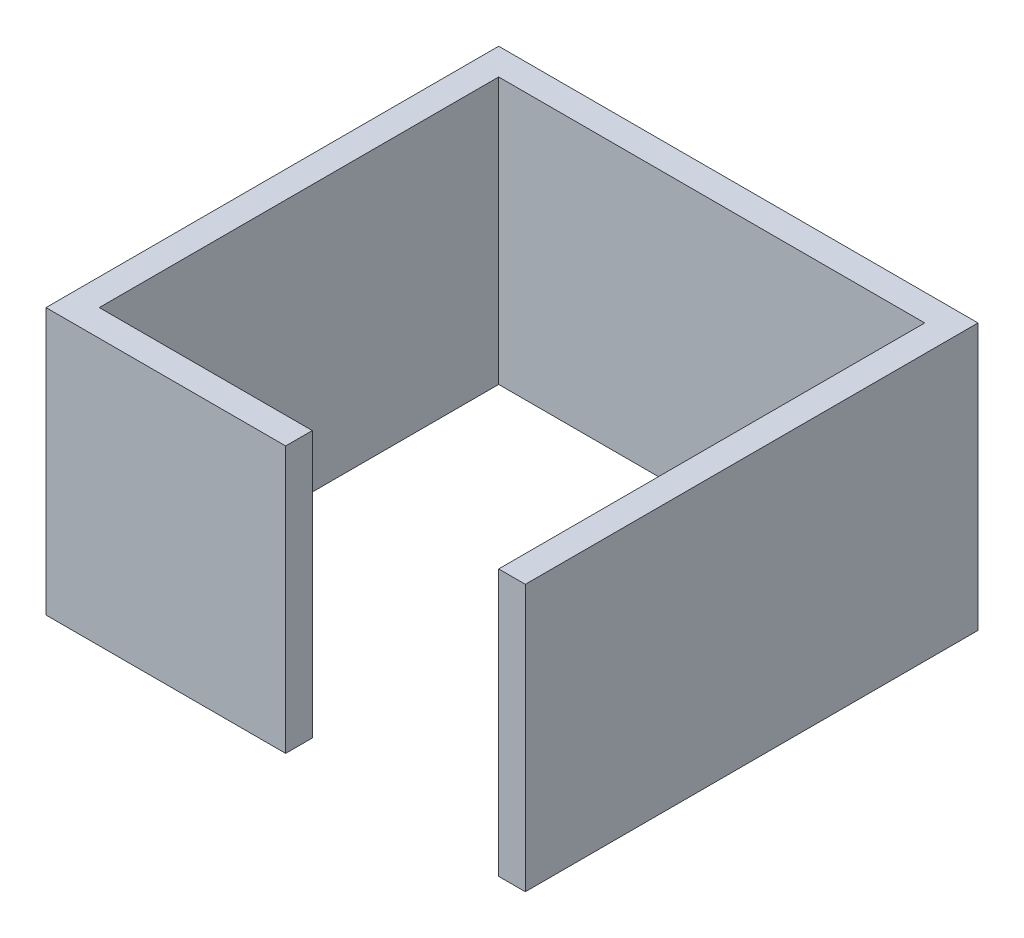
SolidWorks part; units mm, degrees
ref_plane "Front Plane" through (0, 0, 0) normal (0, 0, 1) x (1, 0, 0)
ref_plane "Top Plane" through (0, 0, 0) normal (0, 1, 0) x (1, 0, 0)
ref_plane "Right Plane" through (0, 0, 0) normal (1, 0, 0) x (0, 0, -1)
sketch "Sketch1" plane through (0, 0, 0) normal (0, 1, 0) x (1, 0, 0)
  line L0 (0, 0) -> (0, 170)
  line L1 (0, 170) -> (-180, 170)
  line L2 (-180, 170) -> (-180, 0)
  line L3 (-180, 0) -> (-170, 0)
  line L4 (-170, 0) -> (-170, 160)
  line L5 (-170, 160) -> (-10, 160)
  line L6 (-10, 160) -> (-10, 0)
  line L7 (-10, 0) -> (0, 0)
  dimension "D1" = 170
  dimension "D2" = 180
  dimension "D3" = 10
  dimension "D4" = 10
  dimension "D5" = 10
extrude "Boss-Extrude1" add sketch "Sketch1" along normal blind 100
sketch "Sketch2" plane through (-170, 0, 0) normal (1, 0, 0) x (0, 0, -1)
  line L0 (0, 0) -> (170, 0) construction
  line L1 (0, 100) -> (10, 100)
  line L2 (0, 100) -> (0, 0)
  line L3 (0, 0) -> (10, 0)
  line L4 (10, 100) -> (10, 0)
  dimension "D1" = 10
extrude "Boss-Extrude2" add sketch "Sketch2" along normal blind 80
